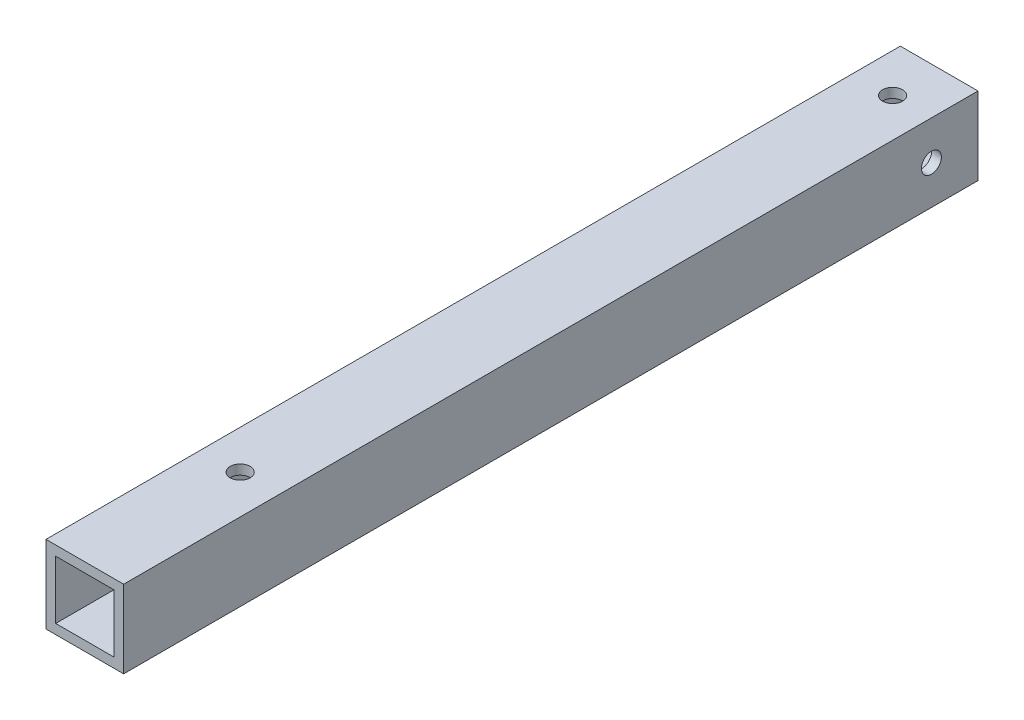
SolidWorks part; units mm, degrees
material "1060 Alloy"
ref_plane "Front Plane" through (0, 0, 0) normal (0, 0, 1) x (1, 0, 0)
ref_plane "Top Plane" through (0, 0, 0) normal (0, 1, 0) x (1, 0, 0)
ref_plane "Right Plane" through (0, 0, 0) normal (1, 0, 0) x (0, 0, -1)
sketch "Sketch2" plane through (0, 0, 0) normal (0, 0, 1) x (1, 0, 0)
  line L1 (12.7, -12.7) -> (-12.7, -12.7)
  line L2 (12.7, -12.7) -> (12.7, 12.7)
  line L3 (12.7, 12.7) -> (-12.7, 12.7)
  line L4 (-12.7, -12.7) -> (-12.7, 12.7)
  line L5 (12.7, -12.7) -> (-12.7, 12.7) construction
  line L6 (12.7, 12.7) -> (-12.7, -12.7) construction
  point P0 (0, 0)
  dimension "D1" = 25.4
extrude "Boss-Extrude1" add sketch "Sketch2" along normal blind 279.4 contours L4 L3 L2 L1
sketch "Sketch4" plane through (0, 0, 0) normal (0, 0, 1) x (1, 0, 0)
  line L0 (12.7, -12.7) -> (12.7, 12.7) construction
  line L1 (-9.525, -9.525) -> (9.525, -9.525)
  line L2 (-9.525, -9.525) -> (-9.525, 9.525)
  line L3 (-9.525, 9.525) -> (9.525, 9.525)
  line L4 (9.525, -9.525) -> (9.525, 9.525)
  line L5 (-9.525, -9.525) -> (9.525, 9.525) construction
  line L6 (-9.525, 9.525) -> (9.525, -9.525) construction
  line L7 (12.7, 12.7) -> (-12.7, 12.7) construction
  point P0 (0, 0)
  dimension "D1" = 3.175
  dimension "D2" = 3.175
extrude "Cut-Extrude1" cut sketch "Sketch4" along normal through all
sketch "Sketch5" plane through (0, 12.7, 0) normal (0, 1, 0) x (1, 0, 0)
  line L0 (12.7, 0) -> (-12.7, 0) construction
  circle A0 centre (0, -15.24) radius 3.2639
  point P5 (0, 0)
  dimension "D1" = 6.5278
  dimension "D2" = 15.24
extrude "Cut-Extrude2" cut sketch "Sketch5" against normal through all
sketch "Sketch6" plane through (0, 12.7, 0) normal (0, 1, 0) x (1, 0, 0)
  line L0 (12.7, -279.4) -> (-12.7, -279.4) construction
  circle A0 centre (0, -228.6) radius 3.2639
  point P4 (0, -279.4)
  dimension "D1" = 6.5278
  dimension "D2" = 50.8
extrude "Cut-Extrude3" cut sketch "Sketch6" against normal through all
sketch "Sketch7" plane through (-12.7, 0, 0) normal (-1, 0, 0) x (0, 0, 1)
  line L0 (0, -12.7) -> (0, 12.7) construction
  circle A0 centre (15.24, 0) radius 3.2639
  point P4 (0, 0)
  dimension "D2" = 6.5278
  dimension "D1" = 15.24
extrude "Cut-Extrude4" cut sketch "Sketch7" against normal through all contours A0
